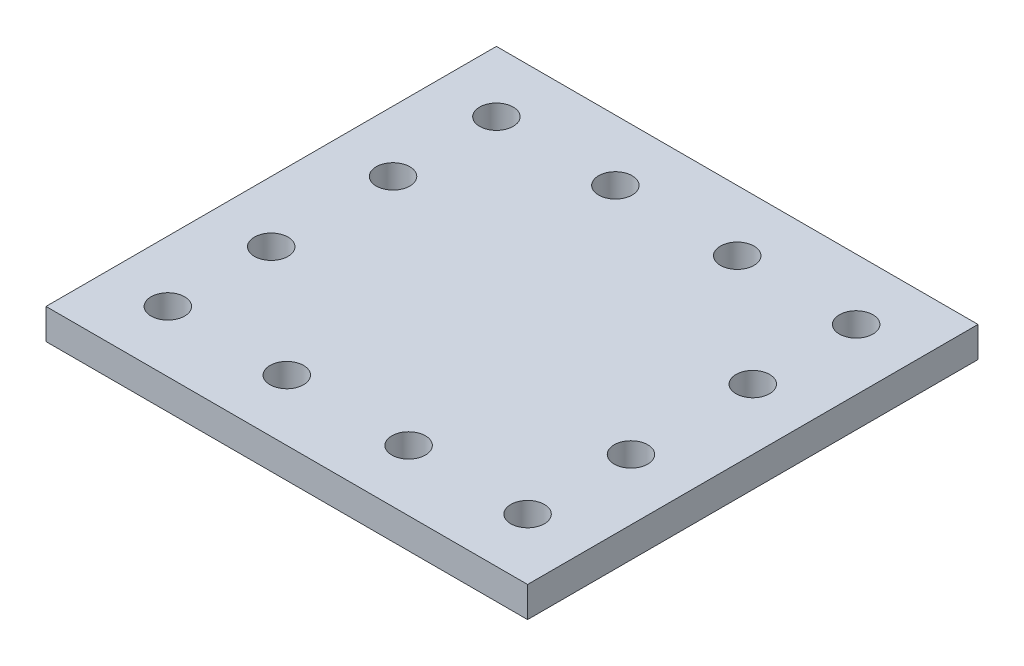
SolidWorks part; units mm, degrees
ref_plane "Front Plane" through (0, 0, 0) normal (0, 0, 1) x (1, 0, 0)
ref_plane "Top Plane" through (0, 0, 0) normal (0, 1, 0) x (1, 0, 0)
ref_plane "Right Plane" through (0, 0, 0) normal (1, 0, 0) x (0, 0, -1)
sketch "Sketch1" plane through (0, 0, 0) normal (0, 1, 0) x (1, 0, 0)
  line L1 (0, 0) -> (100.4, 0)
  line L2 (0, 0) -> (0, 93.9)
  line L3 (0, 93.9) -> (100.4, 93.9)
  line L4 (100.4, 0) -> (100.4, 93.9)
  dimension "D1" = 100.4
  dimension "D2" = 93.9
extrude "Boss-Extrude1" add sketch "Sketch1" along normal blind 6.35
sketch "Sketch2" plane through (0, 6.35, 0) normal (0, 1, 0) x (1, 0, 0)
  line L0 (100.4, 93.9) -> (0, 93.9) construction
  line L1 (0, 93.9) -> (0, 0) construction
  line L2 (50.2, 93.9) -> (50.2, 0) construction
  line L3 (0, 0) -> (100.4, 0) construction
  line L4 (100.4, 46.95) -> (0, 46.95) construction
  line L5 (100.4, 0) -> (100.4, 93.9) construction
  circle A0 centre (12.7, 81.2) radius 3.5
  circle A1 centre (12.7, 12.7) radius 3.5
  circle A2 centre (87.7, 12.7) radius 3.5
  circle A3 centre (87.7, 81.2) radius 3.5
  dimension "D1" = 7
  dimension "D2" = 12.7
  dimension "D3" = 12.7
extrude "Cut-Extrude1" cut sketch "Sketch2" against normal blind 6.35
sketch "Sketch4" plane through (0, 6.35, 0) normal (0, 1, 0) x (1, 0, 0)
  line L0 (50.2, 93.9) -> (50.2, 0) construction
  line L1 (100.4, 93.9) -> (0, 93.9) construction
  line L2 (0, 0) -> (100.4, 0) construction
  line L3 (100.4, 46.95) -> (0, 46.95) construction
  line L4 (100.4, 0) -> (100.4, 93.9) construction
  line L5 (0, 93.9) -> (0, 0) construction
  line L6 (12.7, 77.7) -> (12.7, 16.2) construction
  line L7 (16.2, 12.7) -> (84.2, 12.7) construction
  line L8 (87.7, 16.2) -> (87.7, 77.7) construction
  line L9 (16.2, 81.2) -> (84.2, 81.2) construction
  circle A0 centre (12.7, 81.2) radius 3.5 construction
  circle A1 centre (12.7, 12.7) radius 3.5 construction
  circle A2 centre (87.7, 12.7) radius 3.5 construction
  circle A3 centre (87.7, 81.2) radius 3.5 construction
  circle A4 centre (12.7, 59.65) radius 3.5
  circle A5 centre (12.7, 34.25) radius 3.5
  circle A6 centre (87.7, 34.25) radius 3.5
  circle A7 centre (87.7, 59.65) radius 3.5
  circle A8 centre (37.5, 81.2) radius 3.5
  circle A9 centre (62.9, 81.2) radius 3.5
  circle A10 centre (62.9, 12.7) radius 3.5
  circle A11 centre (37.5, 12.7) radius 3.5
  dimension "D1" = 7
  dimension "D2" = 12.7
  dimension "D3" = 7
  dimension "D4" = 12.7
extrude "Cut-Extrude2" cut sketch "Sketch4" against normal blind 6.35
